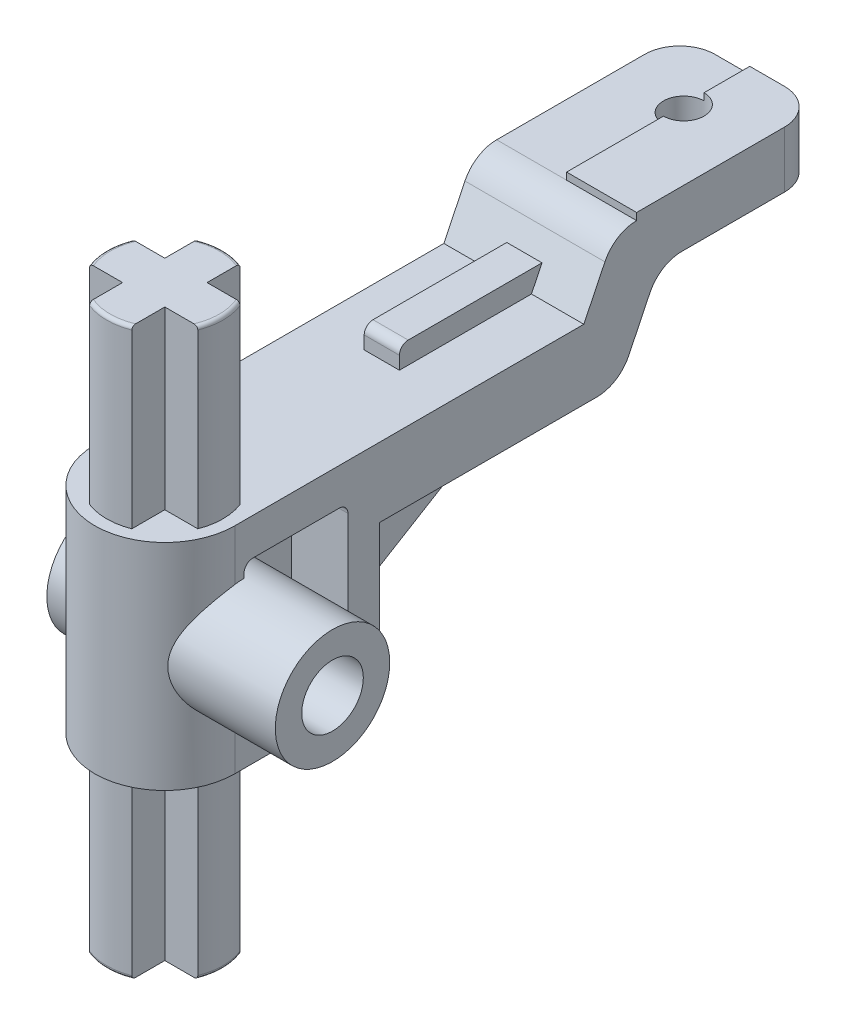
SolidWorks part; units mm, degrees
ref_plane "Alzado" through (0, 0, 0) normal (0, 0, 1) x (1, 0, 0)
ref_plane "Planta" through (0, 0, 0) normal (0, 1, 0) x (1, 0, 0)
ref_plane "Vista lateral" through (0, 0, 0) normal (1, 0, 0) x (0, 0, -1)
sketch "Croquis1" plane through (0, 0, 0) normal (1, 0, 0) x (0, 0, -1)
  line L0 (0, 0) -> (0, 12.2)
  line L1 (0, 12.2) -> (23.8, 12.2)
  line L2 (23.8, 12.2) -> (25.5432, 15.8)
  line L3 (25.5432, 15.8) -> (37.2, 15.8)
  line L4 (37.2, 15.8) -> (37.2, 13)
  line L5 (37.2, 13) -> (28.1, 13)
  line L6 (28.1, 13) -> (25.8, 8.25)
  line L7 (25.8, 8.25) -> (12.2, 8.25)
  line L8 (12.2, 8.25) -> (12.2, 0)
  line L9 (12.2, 0) -> (0, 0)
  dimension "D1" = 37.2
  dimension "D2" = 15.8
  dimension "D3" = 12.2
  dimension "D4" = 12.2
  dimension "D5" = 25.8
  dimension "D6" = 8.25
  dimension "D7" = 2.8
  dimension "D8" = 23.8
  dimension "D9" = 9.1
extrude "Saliente-Extruir1" add sketch "Croquis1" along normal blind 7.95
sketch "Croquis2" plane through (0, 15.8, 0) normal (0, 1, 0) x (1, 0, 0)
  line L0 (0, 23.8) -> (0, 0) construction
  line L1 (7.95, 23.8) -> (7.95, 0) construction
  line L2 (7.95, 0) -> (0, 0) construction
  line L3 (0, 3.975) -> (0, -1.0234)
  line L4 (0, -1.0234) -> (7.95, -1.0234)
  line L5 (7.95, -1.0234) -> (7.95, 3.975)
  arc A0 (0, 3.975) -> (7.95, 3.975) centre (3.975, 3.975) ccw
extrude "Cortar-Extruir1" cut sketch "Croquis2" against normal through all
ref_plane "Plano1" through (3.975, 0, 0) normal (-1, 0, 0) x (0, 0, 1)
sketch "Croquis3" plane through (3.975, 0, 0) normal (-1, 0, 0) x (0, 0, 1)
  line L0 (-23.8, 12.2) -> (-23.8, 8.25) construction
  line L1 (-12.2, 8.25) -> (-25.8, 8.25) construction
  line L2 (-23.8, 8.25) -> (-12.2, 1.25)
  line L3 (-12.2, 0) -> (-12.2, 8.25) construction
  line L4 (-12.2, 1.25) -> (-12.2, 8.25)
  line L5 (-12.2, 8.25) -> (-23.8, 8.25)
  dimension "D1" = 7
extrude "Saliente-Extruir2" add sketch "Croquis3" along normal mid plane 1.9
fillet "Redondeo1" radius 2 5 edges at (7.95, 14.4, -37.2) (0, 14.4, -37.2) (3.975, 13, -28.1) (3.975, 15.8, -25.5432) (3.975, 8.25, -25.8)
sketch "Croquis5" plane through (3.975, 0, 0) normal (-1, 0, 0) x (0, 0, 1)
  line L0 (-24.3984, 8.25) -> (-24.3984, 13.4358) construction
  line L1 (-24.9968, 14.6716) -> (-23.8, 12.2) construction
  line L2 (-24.3984, 13.4358) -> (-16.3, 13.4358)
  line L3 (-16.3, 13.4358) -> (-16.3, 10.4358)
  line L4 (-16.3, 10.4358) -> (-24.3984, 10.4358)
  line L5 (-12.2, 8.25) -> (-24.5463, 8.25) construction
  line L6 (-24.3984, 13.4358) -> (-24.3984, 10.4358)
  line L7 (-37.2, 13) -> (-37.2, 15.8) construction
  dimension "D1" = 3
  dimension "D2" = 20.9
extrude "Saliente-Extruir3" add sketch "Croquis5" along normal mid plane 2
fillet "Redondeo2" radius 0.5 1 edges at (3.975, 13.4358, -16.3)
fillet "Redondeo3" radius 1 1 edges at (3.975, 0, -12.2)
ref_plane "Plano2" through (0, 6.1, 0) normal (0, 1, 0) x (1, 0, 0)
sketch "Croquis6" plane through (0, 6.1, 0) normal (0, 1, 0) x (1, 0, 0)
  line L0 (2.775, 7.0491) -> (2.775, 5.175)
  line L1 (2.775, 3.975) -> (5.175, 3.975) construction
  line L2 (5.175, 5.175) -> (5.175, 7.0491)
  line L3 (3.975, 7.275) -> (3.975, 3.975) construction
  line L4 (7.0491, 5.175) -> (5.175, 5.175)
  line L5 (5.175, 2.775) -> (7.0491, 2.775)
  line L6 (5.175, 0.9009) -> (5.175, 2.775)
  line L7 (2.775, 2.775) -> (2.775, 0.9009)
  line L8 (0.9009, 2.775) -> (2.775, 2.775)
  line L9 (2.775, 5.175) -> (0.9009, 5.175)
  arc A0 (5.175, 7.0491) -> (2.775, 7.0491) centre (3.975, 3.975) ccw
  arc A1 (0, 3.975) -> (7.95, 3.975) centre (3.975, 3.975) ccw construction
  arc A2 (7.0491, 2.775) -> (7.0491, 5.175) centre (3.975, 3.975) ccw
  arc A3 (2.775, 0.9009) -> (5.175, 0.9009) centre (3.975, 3.975) ccw
  arc A4 (0.9009, 5.175) -> (0.9009, 2.775) centre (3.975, 3.975) ccw
  point P24 (3.975, 3.975)
  dimension "D1" = 6.6
  dimension "D2" = 2.4
  dimension "D3" = 1.2
  dimension "D4" = 4
extrude "Saliente-Extruir5" add sketch "Croquis6" along normal mid plane 32.15
sketch "Croquis8" plane through (0, 15.8, 0) normal (0, 1, 0) x (1, 0, 0)
  line L0 (3.975, 37.2) -> (5.95, 37.2)
  line L1 (5.95, 37.2) -> (2, 37.2) construction
  line L2 (5.95, 37.2) -> (7.95, 37.2)
  line L3 (7.95, 26.7969) -> (7.95, 37.2)
  line L4 (3.975, 37.2) -> (3.975, 26.7969)
  line L5 (0, 26.7969) -> (7.95, 26.7969) construction
  line L6 (3.975, 26.7969) -> (7.95, 26.7969)
extrude "Saliente-Extruir6" add sketch "Croquis8" along normal blind 0.4 and the other way up to vertex
fillet "Redondeo4" radius 2 1 edges at (7.95, 14.6, -37.2)
sketch "Croquis9" plane through (0, 16.2, 0) normal (0, 1, 0) x (1, 0, 0)
  line L0 (3.975, 37.2) -> (3.975, 26.7969) construction
  circle A0 centre (3.975, 33.45) radius 1.15
  dimension "D1" = 2.3
  dimension "D2" = 3.75
extrude "Cortar-Extruir2" cut sketch "Croquis9" against normal up to next
fillet "Redondeo5" radius 0.2 8 edges at (0.675, -9.975, -3.975) (3.975, -9.975, -0.675) (7.275, -9.975, -3.975) (3.975, -9.975, -7.275) (7.275, 22.175, -3.975) (3.975, 22.175, -0.675) (0.675, 22.175, -3.975) (3.975, 22.175, -7.275)
ref_plane "Plano4" through (3.975, 0, 0) normal (1, 0, 0) x (0, 0, -1)
sketch "Croquis10" plane through (3.975, 0, 0) normal (1, 0, 0) x (0, 0, -1)
  line L0 (12.2, 1) -> (12.2, 8.25) construction
  circle A0 centre (4.5, 6.1) radius 3.25
  dimension "D1" = 6.5
  dimension "D2" = 7.7
extrude "Saliente-Extruir7" add sketch "Croquis10" along normal blind 9 and the other way up to surface other way up to face at (0, 9.6767, -21.242)
sketch "Croquis11" plane through (0, 0, 0) normal (-1, 0, 0) x (0, 0, 1)
  line L0 (-10.4, 10.1) -> (-4.5, 10.1)
  line L1 (-10.4, 10.1) -> (-10.4, 1.8)
  line L2 (-10.4, 1.8) -> (-4.5, 1.8)
  line L4 (-4.5, 2.85) -> (-4.5, 1.8)
  line L6 (-4.5, 10.1) -> (-4.5, 9.35)
  line L7 (-12.2, 1) -> (-12.2, 8.25) construction
  line L8 (-3.975, 0) -> (-11.2, 0) construction
  arc A0 (-4.5, 9.35) -> (-4.5, 2.85) centre (-4.5, 6.1) ccw
  arc A1 (-3.975, 2.8927) -> (-3.975, 9.3073) centre (-4.5, 6.1) ccw construction
  dimension "D1" = 1.8
  dimension "D2" = 1.8
  dimension "D3" = 8.3
extrude "Cortar-Extruir3" cut sketch "Croquis11" against normal blind 3.2
fillet "Redondeo6" radius 0.5 4 edges at (1.6, 1.8, -4.5) (1.6, 1.8, -10.4) (1.6, 10.1, -10.4) (1.6, 10.1, -4.5)
mirror "Simetría4" about plane through (3.975, 0, 0) normal (1, 0, 0) of "Redondeo6", "Cortar-Extruir3"
sketch "Croquis12" plane through (12.975, 0, 0) normal (1, 0, 0) x (0, 0, -1)
  circle A0 centre (4.5, 6.1) radius 1.75
  circle A1 centre (4.5, 6.1) radius 3.25 construction
  dimension "D1" = 3.5
extrude "Cortar-Extruir4" cut sketch "Croquis12" against normal up to next
ref_plane "Plano5" through (-10, 0, 0) normal (-1, 0, 0) x (0, 0, 1)
mirror "Simetría6" about plane through (-10, 0, 0) normal (-1, 0, 0) of bodies 114
ref_plane "Plano6" through (-10, 0, 0) normal (1, 0, 0) x (0, 0, -1)
sketch "Croquis13" plane through (-10, 0, 0) normal (1, 0, 0) x (0, 0, -1)
  line L1 (-0.968, -11.2574) -> (40.1222, -11.2574)
  line L2 (-0.968, -11.2574) -> (-0.968, 23.6758)
  line L3 (-0.968, 23.6758) -> (40.1222, 23.6758)
  line L4 (40.1222, -11.2574) -> (40.1222, 23.6758)
extrude "Cortar-Extruir6" cut sketch "Croquis13" against normal blind 33 contours L3 L4 L1 L2
